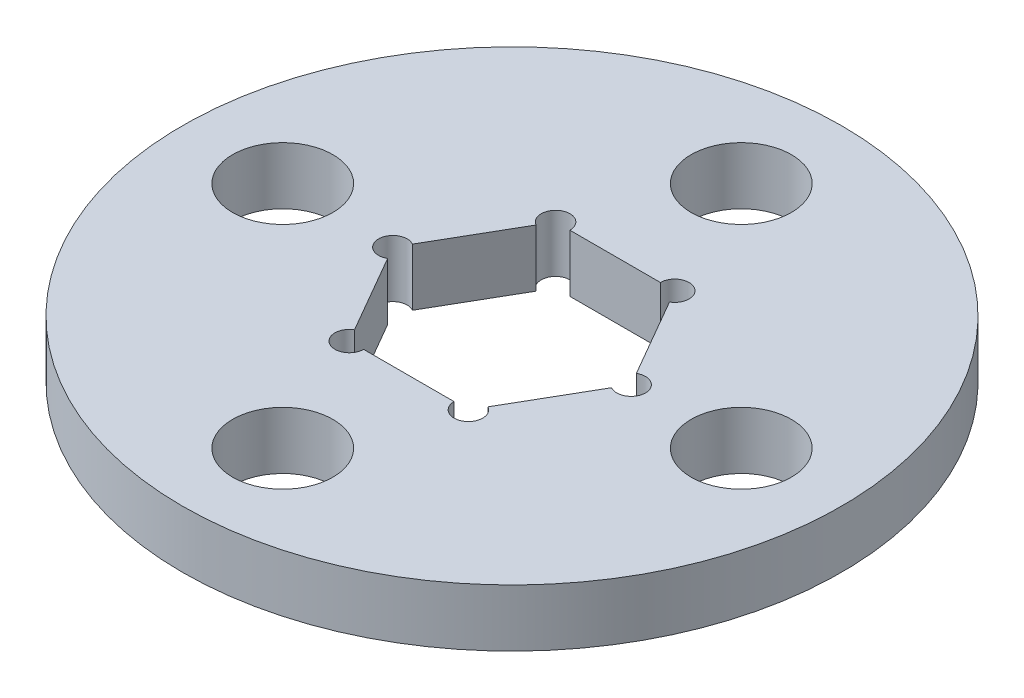
SolidWorks part; units mm, degrees
ref_plane "Front Plane" through (0, 0, 0) normal (0, 0, 1) x (1, 0, 0)
ref_plane "Top Plane" through (0, 0, 0) normal (0, 1, 0) x (1, 0, 0)
ref_plane "Right Plane" through (0, 0, 0) normal (1, 0, 0) x (0, 0, -1)
sketch "Sketch1" plane through (0, 0, 0) normal (0, 1, 0) x (1, 0, 0)
  line L1 (2.0785, 3.6) -> (-2.0785, 3.6)
  line L2 (-2.0785, 3.6) -> (-4.1569, 0)
  line L3 (-4.1569, 0) -> (-2.0785, -3.6)
  line L4 (-2.0785, -3.6) -> (2.0785, -3.6)
  line L5 (2.0785, -3.6) -> (4.1569, 0)
  line L6 (4.1569, 0) -> (2.0785, 3.6)
  circle A0 centre (0, 0) radius 3.6 construction
  circle A1 centre (0, 8) radius 1.75
  circle A2 centre (8, 0) radius 1.75
  circle A3 centre (0, -8) radius 1.75
  circle A4 centre (-8, 0) radius 1.75
  circle A5 centre (0, 0) radius 11.5
  point P20 (0, 0)
  dimension "D1" = 7.2
  dimension "D3" = 16
  dimension "D4" = 3.5
  dimension "D5" = 23
  dimension "D2" = 4
extrude "Boss-Extrude1" add sketch "Sketch1" along normal blind 2
sketch "Sketch2" plane through (0, 0, 0) normal (0, -1, 0) x (1, 0, 0)
  circle A0 centre (-2.0785, 3.6) radius 0.5
  circle A1 centre (2.0785, 3.6) radius 0.5
  circle A2 centre (4.1569, 0) radius 0.5
  circle A3 centre (2.0785, -3.6) radius 0.5
  circle A4 centre (-2.0785, -3.6) radius 0.5
  circle A5 centre (-4.1569, 0) radius 0.5
  point P16 (0, 0)
  dimension "D2" = 1
  dimension "D1" = 6
extrude "Cut-Extrude1" cut sketch "Sketch2" against normal through all both and the other way through all
